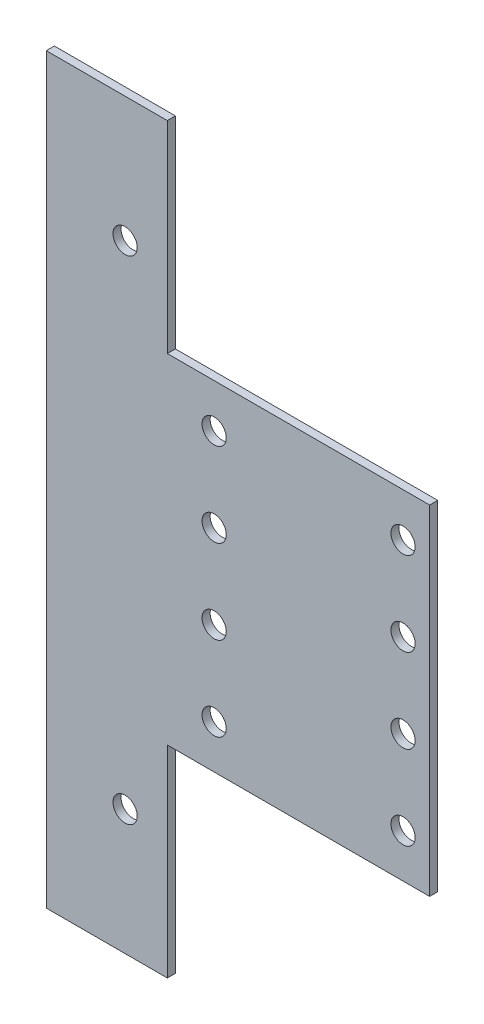
SolidWorks part; units mm, degrees
ref_plane "Спереди" through (0, 0, 0) normal (0, 0, 1) x (1, 0, 0)
ref_plane "Сверху" through (0, 0, 0) normal (0, 1, 0) x (1, 0, 0)
ref_plane "Справа" through (0, 0, 0) normal (1, 0, 0) x (0, 0, -1)
sketch "Эскиз1" plane through (0, 0, 0) normal (0, 0, 1) x (1, 0, 0)
  line L0 (-23.75, 46) -> (-23.75, -46)
  line L1 (-8.75, 21) -> (-8.75, 46)
  line L2 (-8.75, 46) -> (-23.75, 46)
  line L3 (-23.75, -46) -> (-8.75, -46)
  line L4 (-8.75, -46) -> (-8.75, -21)
  line L5 (-8.75, -21) -> (23.75, -21)
  line L6 (23.75, -21) -> (23.75, 21)
  line L7 (23.75, 21) -> (-8.75, 21)
  circle A0 centre (-13.9867, 30.5) radius 1.5
  circle A1 centre (-13.9867, -30.5) radius 1.5
  circle A2 centre (-2.95, -15.6) radius 1.5
  circle A3 centre (-2.95, -5.2) radius 1.5
  circle A4 centre (-2.95, 5.2) radius 1.5
  circle A5 centre (-2.95, 15.6) radius 1.5
  circle A6 centre (20.45, 15.6) radius 1.5
  circle A7 centre (20.45, 5.2) radius 1.5
  circle A8 centre (20.45, -5.2) radius 1.5
  circle A9 centre (20.45, -15.6) radius 1.5
extrude "Бобышка-Вытянуть1" add sketch "Эскиз1" along normal blind 1
